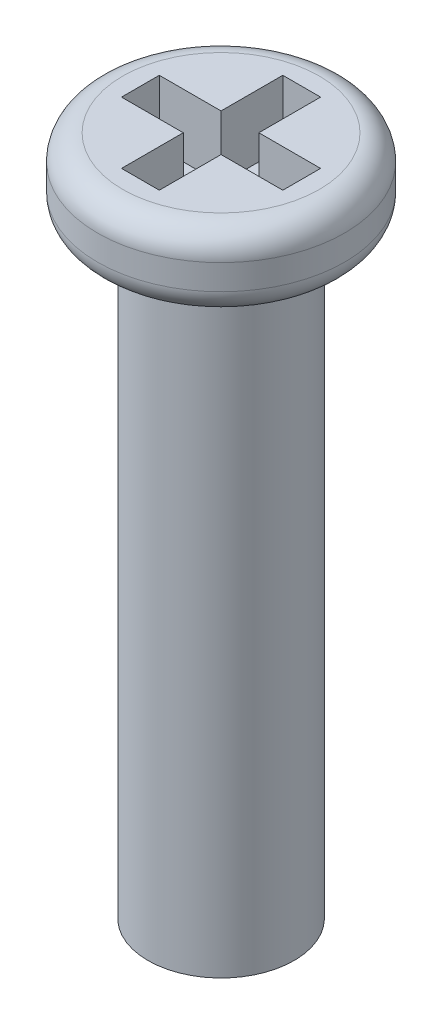
SolidWorks part; units mm, degrees
ref_plane "Front Plane" through (0, 0, 0) normal (0, 0, 1) x (1, 0, 0)
ref_plane "Top Plane" through (0, 0, 0) normal (0, 1, 0) x (1, 0, 0)
ref_plane "Right Plane" through (0, 0, 0) normal (1, 0, 0) x (0, 0, -1)
sketch "Sketch1" plane through (0, 0, 0) normal (0, 1, 0) x (1, 0, 0)
  circle A0 centre (0, 0) radius 1.45
  dimension "D1" = 2.9
extrude "Boss-Extrude1" add sketch "Sketch1" along normal blind 12
sketch "Sketch2" plane through (0, 12, 0) normal (0, 1, 0) x (1, 0, 0)
  circle A0 centre (0, 0) radius 2.45
  dimension "D1" = 4.9
extrude "Boss-Extrude2" add sketch "Sketch2" along normal blind 1.5
fillet "Fillet1" radius 0.5 2 edges at (0, 12, 2.45) (0, 13.5, 2.45)
sketch "Sketch3" plane through (0, 13.5, 0) normal (0, 1, 0) x (1, 0, 0)
  line L1 (-0.375, 1.6) -> (0.375, 1.6)
  line L2 (-0.375, 1.6) -> (-0.375, -1.6)
  line L3 (-0.375, -1.6) -> (0.375, -1.6)
  line L4 (0.375, 1.6) -> (0.375, -1.6)
  line L5 (-1.6, 0.375) -> (1.6, 0.375)
  line L6 (-1.6, 0.375) -> (-1.6, -0.375)
  line L7 (-1.6, -0.375) -> (1.6, -0.375)
  line L8 (1.6, 0.375) -> (1.6, -0.375)
  dimension "D1" = 0.75
  dimension "D2" = 0.75
  dimension "D3" = 3.2
  dimension "D4" = 3.2
  dimension "D5" = 1.6
  dimension "D6" = 0.375
  dimension "D7" = 1.6
  dimension "D8" = 0.375
extrude "Cut-Extrude1" cut sketch "Sketch3" against normal blind 1.25 contours L2 L5 L4 L1 | L2 L7 L4 L5 | L7 L2 L3 L4 | L8 L5 L4 L7 | L6 L7 L2 L5
fillet "Fillet4" radius 0.5 4 edges at (0, 12.25, 1.6) (1.6, 12.25, 0) (-1.6, 12.25, 0) (0, 12.25, -1.6)
